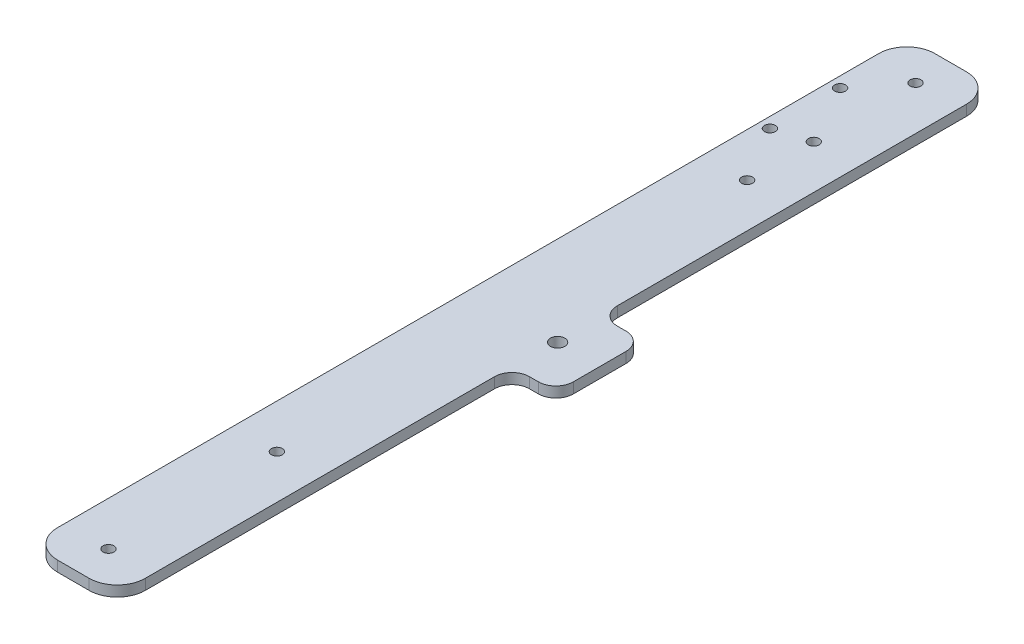
SolidWorks part; units mm, degrees
material "Thornel Mat VMA"
ref_plane "前视基准面" through (0, 0, 0) normal (0, 0, 1) x (1, 0, 0)
ref_plane "上视基准面" through (0, 0, 0) normal (0, 1, 0) x (1, 0, 0)
ref_plane "右视基准面" through (0, 0, 0) normal (1, 0, 0) x (0, 0, -1)
sketch "草图1" plane through (0, 0, 0) normal (0, 1, 0) x (1, 0, 0)
  line L1 (-12.5, 125) -> (12.5, 125)
  line L2 (-12.5, 125) -> (-12.5, -125)
  line L3 (-12.5, -125) -> (12.5, -125)
  line L4 (12.5, 125) -> (12.5, -125)
  line L5 (-12.5, 125) -> (12.5, -125) construction
  line L6 (-12.5, -125) -> (12.5, 125) construction
  point P0 (0, 0)
  dimension "D1" = 250
  dimension "D2" = 25
extrude "凸台-拉伸1" add sketch "草图1" along normal blind 3
ref_plane "基准面1" through (0, 0, 0) normal (0, -1, 0) x (-1, 0, 0)
sketch "草图2" plane through (0, 0, 0) normal (0, -1, 0) x (-1, 0, 0)
  circle A0 centre (0, 115) radius 1.55
  circle A1 centre (0, 67) radius 1.55
  circle A2 centre (0, -67) radius 1.55
  circle A3 centre (0, -115) radius 1.55
  dimension "D1" = 3.1
  dimension "D2" = 3.1
  dimension "D3" = 3.1
  dimension "D4" = 3.1
extrude "切除-拉伸1" cut sketch "草图2" against normal blind 3
sketch "草图3" plane through (0, 0, 0) normal (0, -1, 0) x (-1, 0, 0)
  line L1 (12.5, 125) -> (12.5, -125) construction
  line L2 (-12.5, 125) -> (12.5, 125) construction
  circle A0 centre (9.5, 83) radius 1.55
  circle A1 centre (9.5, 103) radius 1.55
  point P6 (9.6928, -92.0453)
  dimension "D1" = 22
  dimension "D3" = 3
  dimension "D4" = 3
  dimension "D5" = 3.1
  dimension "D6" = 3.1
  dimension "D2" = 20
extrude "切除-拉伸2" cut sketch "草图3" against normal blind 10
sketch "草图5" plane through (0, 0, 0) normal (0, -1, 0) x (-1, 0, 0)
  line L0 (-12.5, -125) -> (-12.5, 125) construction
  line L1 (-25, -12.5) -> (0, -12.5)
  line L2 (-25, -12.5) -> (-25, 12.5)
  line L3 (-25, 12.5) -> (0, 12.5)
  line L4 (0, -12.5) -> (0, 12.5)
  line L5 (-25, -12.5) -> (0, 12.5) construction
  line L6 (-25, 12.5) -> (0, -12.5) construction
  point P0 (-12.5, 0)
  dimension "D1" = 25
  dimension "D2" = 25
extrude "凸台-拉伸2" add sketch "草图5" against normal through all
sketch "草图6" plane through (0, 0, 0) normal (0, -1, 0) x (-1, 0, 0)
  line L0 (-25, -12.5) -> (-12.5, -12.5) construction
  line L1 (-25, 12.5) -> (-25, -12.5) construction
  circle A0 centre (-13, 0) radius 2.05
  dimension "D1" = 12.5
  dimension "D2" = 12
  dimension "D3" = 4.1
extrude "切除-拉伸3" cut sketch "草图6" against normal blind 10
sketch "草图7" plane through (0, 0, 0) normal (0, -1, 0) x (-1, 0, 0)
  line L0 (-12.5, 12.5) -> (-12.5, 125) construction
  circle A0 centre (0, 86) radius 1.55
  circle A1 centre (0, 115) radius 1.55 construction
  point P4 (0, 0)
  dimension "D1" = 29
  dimension "D2" = 3.1
  dimension "D3" = 12.5
extrude "切除-拉伸4" cut sketch "草图7" against normal blind 10
fillet "圆角1" radius 5 4 edges at (12.5, 1.5, 12.5) (25, 1.5, 12.5) (12.5, 1.5, -12.5) (25, 1.5, -12.5)
fillet "圆角2" radius 8 4 edges at (-12.5, 1.5, -125) (12.5, 1.5, -125) (-12.5, 1.5, 125) (12.5, 1.5, 125)
